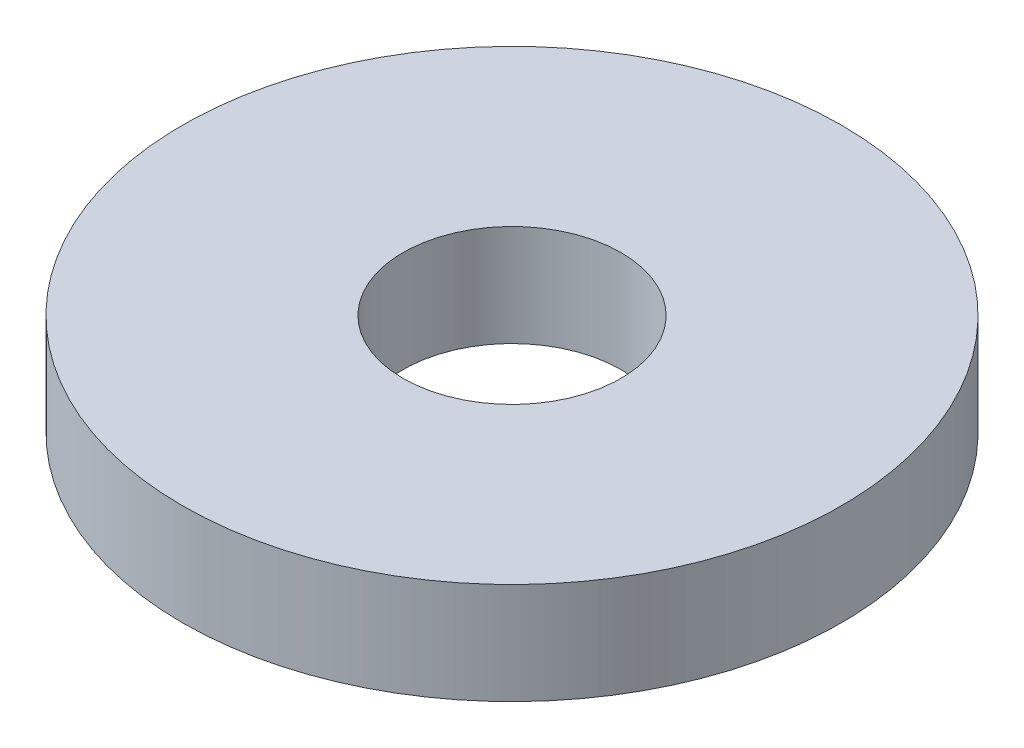
SolidWorks part; units mm, degrees
ref_plane "Front Plane" through (0, 0, 0) normal (0, 0, 1) x (1, 0, 0)
ref_plane "Top Plane" through (0, 0, 0) normal (0, 1, 0) x (1, 0, 0)
ref_plane "Right Plane" through (0, 0, 0) normal (1, 0, 0) x (0, 0, -1)
sketch "Sketch1" plane through (0, 0, 0) normal (0, 1, 0) x (1, 0, 0)
  circle A0 centre (0, 0) radius 6.5
  circle A1 centre (0, 0) radius 2.15
  dimension "D1" = 13
  dimension "D2" = 4.3
extrude "Boss-Extrude1" add sketch "Sketch1" along normal blind 2
